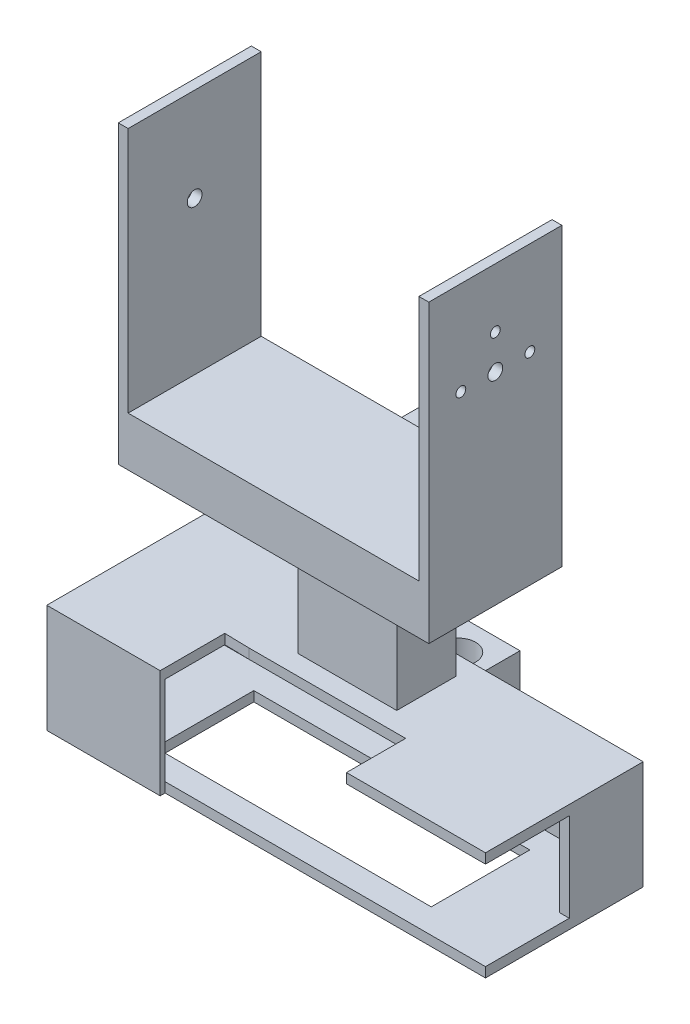
SolidWorks part; units mm, degrees
ref_plane "Front Plane" through (0, 0, 0) normal (0, 0, 1) x (1, 0, 0)
ref_plane "Top Plane" through (0, 0, 0) normal (0, 1, 0) x (1, 0, 0)
ref_plane "Right Plane" through (0, 0, 0) normal (1, 0, 0) x (0, 0, -1)
sketch "Sketch1" plane through (0, 0, 0) normal (0, 1, 0) x (1, 0, 0)
  line L1 (-31.5, -13.5) -> (31.5, -13.5)
  line L2 (-31.5, -13.5) -> (-31.5, 13.5)
  line L3 (-31.5, 13.5) -> (31.5, 13.5)
  line L4 (31.5, -13.5) -> (31.5, 13.5)
  line L5 (-31.5, -13.5) -> (31.5, 13.5) construction
  line L6 (-31.5, 13.5) -> (31.5, -13.5) construction
  point P0 (0, 0)
  dimension "D1" = 63
  dimension "D2" = 27
extrude "Boss-Extrude1" add sketch "Sketch1" along normal blind 60
sketch "Sketch2" plane through (0, 60, 0) normal (0, 1, 0) x (1, 0, 0)
  line L0 (-31.5, 13.5) -> (-29.5, 13.5)
  line L1 (31.5, 13.5) -> (-31.5, 13.5) construction
  line L2 (31.5, 13.5) -> (29.5, 13.5)
  line L3 (-31.5, -13.5) -> (31.5, -13.5) construction
  line L4 (-29.5, 13.5) -> (29.5, 13.5)
  line L5 (-29.5, 13.5) -> (-29.5, -13.5)
  line L6 (-29.5, -13.5) -> (29.5, -13.5)
  line L7 (29.5, 13.5) -> (29.5, -13.5)
  line L8 (-29.5, 13.5) -> (29.5, 13.5)
  line M4 (31.5, 13.5) -> (-31.5, 13.5)
  line M6 (-31.5, -13.5) -> (31.5, -13.5)
  dimension "D1" = 2
  dimension "D2" = 2
  dimension "D3" = 59
extrude "Cut-Extrude1" cut sketch "Sketch2" against normal blind 50 contours L7 L5 M4 M6
sketch "Sketch3" plane through (31.5, 0, 0) normal (1, 0, 0) x (0, 0, -1)
  line L0 (-13.5, 60) -> (13.5, 60)
  line L1 (0, 60) -> (0, 41)
  circle A0 centre (0, 41) radius 1.5
  dimension "D2" = 3
  dimension "D1" = 19
extrude "Cut-Extrude2" cut sketch "Sketch3" against normal blind 65
sketch "Sketch5" plane through (0, 0, 0) normal (0, -1, 0) x (1, 0, 0)
  line L7 (-10, -1.5) -> (-10, -13.5)
  line L8 (31.5, -13.5) -> (-31.5, -13.5) construction
  line L9 (-10, -1.5) -> (10, -1.5)
  line L10 (10, -1.5) -> (10, -13.5)
  line L11 (-10, -13.5) -> (10, -13.5)
  dimension "D1" = 12
  dimension "D2" = 12
  dimension "D3" = 20
extrude "Boss-Extrude2" add sketch "Sketch5" along normal blind 30
sketch "Sketch6" plane through (0, -30, 0) normal (0, -1, 0) x (1, 0, 0)
  line L0 (0, -1.5) -> (0, -13.5)
  line L1 (10, -1.5) -> (-10, -1.5) construction
  line L2 (-10, -13.5) -> (10, -13.5) construction
  line L3 (-10, -7.5) -> (10, -7.5)
  line L4 (-10, -1.5) -> (-10, -13.5) construction
  line L5 (10, -13.5) -> (10, -1.5) construction
  line L7 (44, 14.5) -> (-44, 14.5)
  line L8 (44, 14.5) -> (44, -17.5)
  line L9 (44, -17.5) -> (-44, -17.5)
  line L10 (-44, 14.5) -> (-44, -17.5)
  line L11 (44, 14.5) -> (-44, -17.5) construction
  line L12 (44, -17.5) -> (-44, 14.5) construction
  dimension "D1" = 88
  dimension "D2" = 32
extrude "Boss-Extrude3" add sketch "Sketch6" along normal blind 22 contours L7 L10 L9 L8
sketch "Sketch7" plane through (0, 0, 14.5) normal (0, 0, 1) x (1, 0, 0)
  line L4 (42, -50) -> (-41, -50)
  line L5 (42, -50) -> (42, -32)
  line L6 (42, -32) -> (-41, -32)
  line L7 (-41, -50) -> (-41, -32)
  line L8 (42, -50) -> (-41, -32) construction
  line L9 (42, -32) -> (-41, -50) construction
  point P6 (0.5, -41)
  dimension "D1" = 83
  dimension "D2" = 18
extrude "Cut-Extrude3" cut sketch "Sketch7" against normal blind 30
sketch "Sketch10" plane through (0, -52, 0) normal (0, -1, 0) x (1, 0, 0)
  line L5 (-28, 9.5) -> (28, 9.5)
  line L10 (28, 9.5) -> (28, -10.5)
  line L11 (28, -10.5) -> (-28, -10.5)
  line L12 (-28, 9.5) -> (-28, -10.5)
  dimension "D1" = 20
extrude "Cut-Extrude5" cut sketch "Sketch10" against normal blind 3
sketch "Sketch11" plane through (0, 0, 14.5) normal (0, 0, 1) x (1, 0, 0)
  line L0 (44, -52) -> (-44, -52) construction
  line L1 (-44, -30) -> (-21, -30)
  line L2 (-44, -30) -> (-44, -52)
  line L3 (-44, -52) -> (-21, -52)
  line L4 (-21, -30) -> (-21, -52)
  dimension "D1" = 23
extrude "Boss-Extrude4" add sketch "Sketch11" along normal blind 1
sketch "Sketch12" plane through (44, 0, 0) normal (1, 0, 0) x (0, 0, -1)
  line L1 (-14.5, -52) -> (-14.5, -30) construction
  line L3 (-14.5, -50) -> (2.5, -50)
  line L4 (-14.5, -32) -> (2.5, -32)
  line L5 (2.5, -32) -> (2.5, -50)
  line L6 (-14.5, -32) -> (-14.5, -50)
  dimension "D1" = 17
extrude "Cut-Extrude7" cut sketch "Sketch12" against normal blind 2.5
sketch "Sketch13" plane through (0, -30, 0) normal (0, 1, 0) x (1, 0, 0)
  line L0 (-15.948, -14.5) -> (-15.948, -2.5)
  line L1 (44, -14.5) -> (-21, -14.5) construction
  line L2 (-15.948, -2.5) -> (15.8017, -2.5)
  line L3 (15.8017, -2.5) -> (15.8017, -14.5)
  line L4 (-15.948, -14.5) -> (15.8017, -14.5)
  dimension "D1" = 12
extrude "Cut-Extrude9" cut sketch "Sketch13" against normal blind 2.5
sketch "Sketch16" plane through (0, -30, 0) normal (0, 1, 0) x (1, 0, 0)
  line L0 (-21, -14.5) -> (-21, -2.3899)
  line L1 (-15.948, -2.5) -> (-21, -2.3899)
  line L2 (-21, -14.5) -> (-15.948, -14.5)
  line L3 (-15.948, -14.5) -> (-15.948, -2.5)
extrude "Cut-Extrude10" cut sketch "Sketch16" against normal blind 2.5
sketch "Sketch23" plane through (0, 0, -17.5) normal (0, 0, -1) x (-1, 0, 0)
  line L5 (6, -46) -> (-6, -46)
  line L6 (6, -46) -> (6, -36)
  line L7 (6, -36) -> (-6, -36)
  line L8 (-6, -46) -> (-6, -36)
  line L9 (6, -46) -> (-6, -36) construction
  line L10 (6, -36) -> (-6, -46) construction
  point P10 (0, -41)
  dimension "D1" = 12
  dimension "D2" = 10
extrude "Boss-Extrude7" add sketch "Sketch23" along normal blind 13
sketch "Sketch25" plane through (0, -36, 0) normal (0, 1, 0) x (1, 0, 0)
  circle A0 centre (0, 24) radius 3.5
extrude "Cut-Extrude13" cut sketch "Sketch25" against normal blind 13
sketch "Sketch26" plane through (0, 0, -13.5) normal (0, 0, -1) x (-1, 0, 0)
  line L1 (-29.5, 10) -> (29.5, 10) construction
  line L7 (0, 10) -> (0, 0)
  line L9 (6, 5) -> (-6, 5)
  line L10 (6, 5) -> (6, -5)
  line L11 (6, -5) -> (-6, -5)
  line L12 (-6, 5) -> (-6, -5)
  line L13 (6, 5) -> (-6, -5) construction
  line L14 (6, -5) -> (-6, 5) construction
  dimension "D1" = 10
  dimension "D2" = 12
extrude "Boss-Extrude8" add sketch "Sketch26" along normal blind 17
sketch "Sketch27" plane through (0, 5, 0) normal (0, 1, 0) x (1, 0, 0)
  circle A0 centre (0, 24) radius 3.5
extrude "Cut-Extrude14" cut sketch "Sketch27" against normal blind 17
sketch "Sketch28" plane through (31.5, 0, 0) normal (1, 0, 0) x (0, 0, -1)
  circle A0 centre (0, 48) radius 1
  circle A1 centre (7, 41) radius 1
  circle A2 centre (-7, 41) radius 1
  dimension "D2" = 2
  dimension "D3" = 2
  dimension "D4" = 2
extrude "Cut-Extrude15" cut sketch "Sketch28" against normal blind 10
equation "\"`1\"=10.2224"
